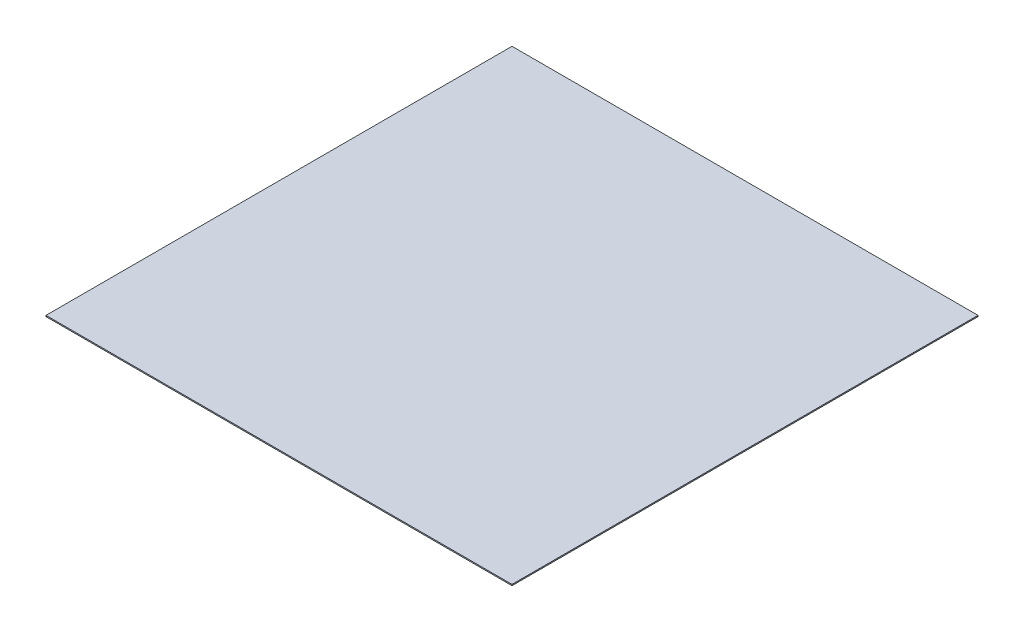
SolidWorks part; units mm, degrees
ref_plane "前视基准面" through (0, 0, 0) normal (0, 0, 1) x (1, 0, 0)
ref_plane "上视基准面" through (0, 0, 0) normal (0, 1, 0) x (1, 0, 0)
ref_plane "右视基准面" through (0, 0, 0) normal (1, 0, 0) x (0, 0, -1)
sketch "Sketch1" plane through (0, 0, 0) normal (0, 1, 0) x (1, 0, 0)
  line L1 (0, 0) -> (400, 0)
  line L2 (0, 0) -> (0, -400)
  line L3 (0, -400) -> (400, -400)
  line L4 (400, 0) -> (400, -400)
  dimension "D1" = 400
  dimension "D2" = 400
extrude "Boss-Extrude1" add sketch "Sketch1" along normal blind 1
